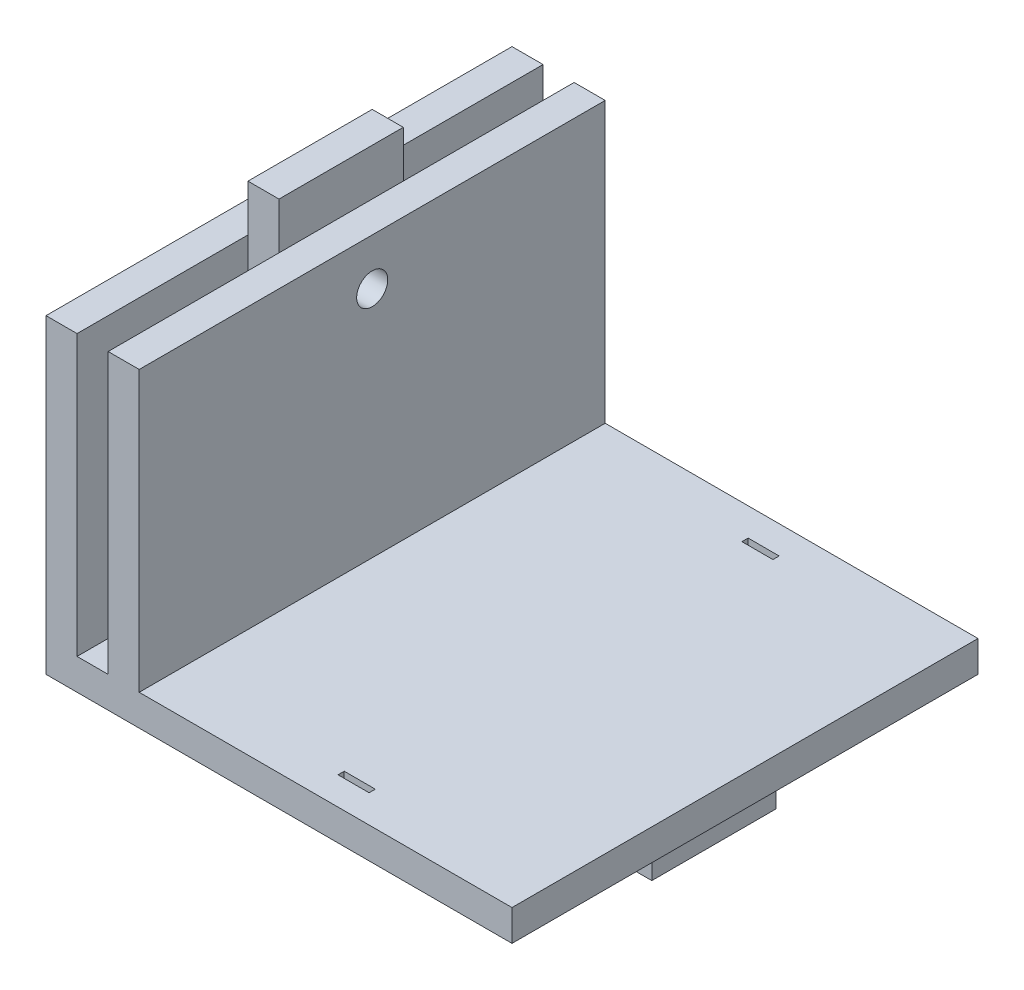
SolidWorks part; units mm, degrees
other "slider2"
other "slider1"
other "encoder"
material "Balsa"
ref_plane "Front Plane" through (0, 0, 0) normal (0, 0, 1) x (1, 0, 0)
ref_plane "Top Plane" through (0, 0, 0) normal (0, 1, 0) x (1, 0, 0)
ref_plane "Right Plane" through (0, 0, 0) normal (1, 0, 0) x (0, 0, -1)
sketch "Sketch1" plane through (0, 0, 0) normal (0, 0, 1) x (1, 0, 0)
  line L0 (20, 10) -> (20, 100)
  line L1 (0, 0) -> (150, 0)
  line L2 (0, 0) -> (0, 10)
  line L3 (10, 10) -> (20, 10)
  line L4 (150, 0) -> (150, 10)
  line L5 (0, 0) -> (10, 0)
  line L6 (0, 0) -> (0, 100)
  line L7 (0, 100) -> (10, 100)
  line L8 (10, 10) -> (10, 100)
  line L9 (150, 10) -> (30, 10)
  line L25 (30, 10) -> (30, 100)
  line L26 (20, 100) -> (30, 100)
  line L27 (30, 0) -> (30, 100) construction
  line L28 (20, 0) -> (20, 100) construction
  line L29 (10, 0) -> (10, 100) construction
  line L30 (30, 10) -> (150, 10)
  point P16 (149.7924, 0)
  point P17 (0, 0)
  dimension "D2" = 10
  dimension "D3" = 10
  dimension "D4" = 100
  dimension "D5" = 10
  dimension "D6" = 10
  dimension "D7" = 150
extrude "Boss-Extrude1" add sketch "Sketch1" along normal blind 150
sketch "Sketch3" plane through (0, 10, 0) normal (0, 1, 0) x (1, 0, 0)
  line L0 (90, -150) -> (90, 0) construction
  line L1 (150, -75) -> (30, -75) construction
  line L2 (95, -141) -> (95, -139)
  line L3 (95, -141) -> (85, -141)
  line L4 (150, 0) -> (30, 0)
  line L5 (30, 0) -> (30, -150)
  line L6 (30, -150) -> (150, -150)
  line L7 (150, -150) -> (150, 0)
  line L8 (150, 0) -> (30, 0)
  line L9 (30, 0) -> (30, -150)
  line L10 (30, -150) -> (150, -150)
  line L11 (150, -150) -> (150, 0)
  line L12 (95, -139) -> (85, -139)
  line L13 (85, -141) -> (85, -139)
  line L14 (90, -139) -> (90, -141) construction
  line L15 (95, -140) -> (85, -140) construction
  line L16 (95, -9) -> (95, -11)
  line L17 (85, -9) -> (85, -11)
  line L18 (95, -11) -> (85, -11)
  line L19 (95, -9) -> (85, -9)
  point P8 (0, 0)
  point P9 (90, -140)
  dimension "D2" = 10
  dimension "D3" = 2
  dimension "D4" = 10
  dimension "D1" = 0
extrude "Cut-Extrude1" cut sketch "Sketch3" against normal blind 10 contours L16 L19 L17 L18 | L3 L13 L12 L2
sketch "Sketch4" plane through (20, 0, 0) normal (-1, 0, 0) x (0, 0, 1)
  line L0 (75, 100) -> (75, 10) construction
  line L1 (150, 55) -> (0, 55) construction
  line L2 (55, 100) -> (55, 65)
  line L3 (95, 100) -> (95, 65)
  line L4 (0, 100) -> (0, 10)
  line L5 (0, 10) -> (150, 10)
  line L6 (150, 10) -> (150, 100)
  line L7 (150, 100) -> (0, 100)
  line L8 (0, 100) -> (0, 10)
  line L9 (0, 10) -> (150, 10)
  line L10 (150, 10) -> (150, 100)
  line L11 (150, 100) -> (0, 100)
  line L12 (95, 100) -> (95, 10) construction
  line L13 (55, 100) -> (55, 10) construction
  arc A0 (55, 65) -> (95, 65) centre (75, 65) ccw
  line M9 (150, 100) -> (0, 100)
  dimension "D4" = 35
  dimension "D1" = 0
  dimension "D2" = 20
  dimension "D3" = 20
extrude "Boss-Extrude2" add sketch "Sketch4" along normal blind 10 separate body contours L2 A0 L3 M9
sketch "Sketch5" plane through (30, 0, 0) normal (1, 0, 0) x (0, 0, -1)
  line L0 (0, 55) -> (-151.4365, 55) construction
  line L1 (-75, 10) -> (-75, 100) construction
  line L4 (0, 10) -> (0, 100)
  line L5 (0, 100) -> (-150, 100)
  line L6 (-150, 100) -> (-150, 10)
  line L7 (-150, 10) -> (0, 10)
  line L8 (0, 10) -> (0, 100)
  line L9 (0, 100) -> (-150, 100)
  line L10 (-150, 100) -> (-150, 10)
  line L11 (-150, 10) -> (0, 10)
  circle A0 centre (-75, 85) radius 5
  point P10 (0, 0)
  dimension "D2" = 10
  dimension "D3" = 15
  dimension "D1" = 0
extrude "Cut-Extrude2" cut sketch "Sketch5" against normal through all contours A0
sketch "Sketch6" plane through (0, 0, 0) normal (0, -1, 0) x (1, 0, 0)
  line L0 (75, 150) -> (75, 0) construction
  line L1 (150, 75) -> (0, 75) construction
  line L2 (30, 55) -> (30, 95)
  line L3 (30, 55) -> (10, 55)
  line L4 (0, 0) -> (150, 0)
  line L5 (150, 0) -> (150, 150)
  line L6 (150, 150) -> (0, 150)
  line L7 (0, 150) -> (0, 0)
  line L8 (0, 0) -> (150, 0)
  line L9 (150, 0) -> (150, 150)
  line L10 (150, 150) -> (0, 150)
  line L11 (0, 150) -> (0, 0)
  line L12 (30, 95) -> (10, 95)
  line L13 (10, 55) -> (10, 95)
  line L14 (20, 95) -> (20, 55) construction
  line L15 (30, 75) -> (10, 75) construction
  line L16 (120, 95) -> (140, 95)
  line L17 (140, 55) -> (140, 95)
  line L18 (120, 55) -> (140, 55)
  line L19 (120, 55) -> (120, 95)
  point P9 (20, 75)
  dimension "D2" = 20
  dimension "D3" = 20
  dimension "D4" = 40
  dimension "D1" = 0
extrude "Boss-Extrude5" add sketch "Sketch6" along normal blind 15 separate body contours L3 L13 L12 L2 | L18 L17 L16 L19
sketch "Sketch7" plane through (0, 0, 95) normal (0, 0, 1) x (1, 0, 0)
  line L0 (20, 0) -> (20, -15) construction
  line L1 (30, -7.5) -> (10, -7.5) construction
  line L3 (22.5, -13) -> (22.5, -15)
  line L4 (30, 0) -> (10, 0)
  line L5 (10, 0) -> (10, -15)
  line L6 (10, -15) -> (30, -15)
  line L7 (30, -15) -> (30, 0)
  line L8 (30, 0) -> (10, 0)
  line L9 (10, 0) -> (10, -15)
  line L10 (10, -15) -> (30, -15)
  line L11 (30, -15) -> (30, 0)
  line L13 (22.5, 0) -> (22.5, -15) construction
  line L14 (17.5, -13) -> (17.5, -15)
  arc A0 (22.5, -13) -> (17.5, -13) centre (20, -8.6699) ccw
  point P9 (17.5, -15)
  point P10 (17.5, -13.2235)
  dimension "D2" = 10
  dimension "D5" = 2
  dimension "D3" = 2.5
  dimension "D1" = 0
  dimension "D4" = 2.5
extrude "Cut-Extrude3" cut sketch "Sketch7" against normal through all contours L3 A0 L14 L10
sketch "Sketch10" plane through (0, 0, 95) normal (0, 0, 1) x (1, 0, 0)
  line L0 (17.5, -13) -> (17.5, -15) construction
  line L1 (22.5, -13) -> (22.5, -15) construction
  line L2 (17.5, -13) -> (17.5, -15)
  line L3 (22.5, -13) -> (22.5, -15)
  line L4 (140, 0) -> (120, 0)
  line L5 (120, 0) -> (120, -15)
  line L6 (120, -15) -> (140, -15)
  line L7 (140, -15) -> (140, 0)
  line L8 (140, 0) -> (120, 0)
  line L9 (120, 0) -> (120, -15)
  line L10 (120, -15) -> (140, -15)
  line L11 (140, -15) -> (140, 0)
  line L12 (30, 0) -> (10, 0)
  line L13 (10, 0) -> (10, -15)
  line L14 (10, -15) -> (30, -15)
  line L15 (30, -15) -> (30, 0)
  line L16 (30, 0) -> (10, 0)
  line L17 (10, 0) -> (10, -15)
  line L18 (10, -15) -> (30, -15)
  line L19 (30, -15) -> (30, 0)
  line L20 (30, 0) -> (120, 0) construction
  line L21 (75, 0) -> (75, -21.4538) construction
  line L22 (132.5, -13) -> (132.5, -15)
  line L23 (127.5, -13) -> (127.5, -15)
  arc A0 (22.5, -13) -> (17.5, -13) centre (20, -8.6699) ccw construction
  arc A1 (22.5, -13) -> (17.5, -13) centre (20, -8.6699) ccw
  arc A2 (127.5, -13) -> (132.5, -13) centre (130, -8.6699) cw
  dimension "D1" = 0
  dimension "D2" = 0
extrude "Cut-Extrude4" cut sketch "Sketch10" against normal through all contours A2 L23 L10 L22
sketch "Sketch11" plane through (0, 100, 0) normal (0, 1, 0) x (1, 0, 0)
  line L4 (20, -95) -> (20, -55)
  line L5 (20, -55) -> (10, -55)
  line L6 (10, -55) -> (10, -95)
  line L7 (10, -95) -> (20, -95)
  line L8 (20, -95) -> (20, -55)
  line L9 (20, -55) -> (10, -55)
  line L10 (10, -55) -> (10, -95)
  line L11 (10, -95) -> (20, -95)
  dimension "D1" = 0
extrude "Boss-Extrude7" add sketch "Sketch11" along normal blind 15 contours L8 L9 L10 L11
